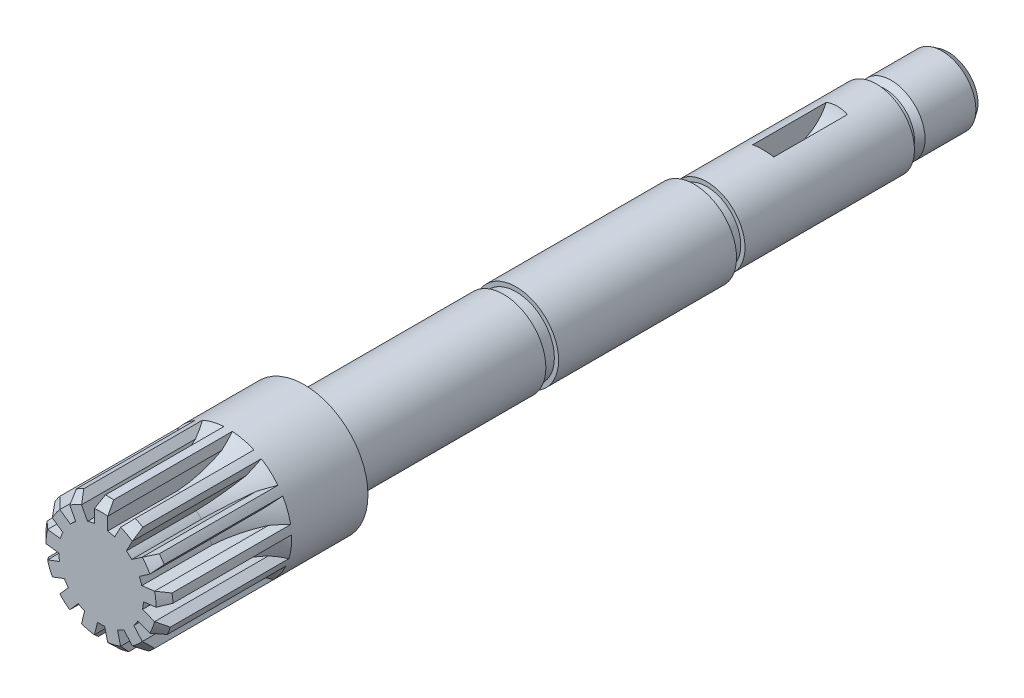
SolidWorks part; units mm, degrees
ref_plane "Спереди" through (0, 0, 0) normal (0, 0, 1) x (1, 0, 0)
ref_plane "Сверху" through (0, 0, 0) normal (0, 1, 0) x (1, 0, 0)
ref_plane "Справа" through (0, 0, 0) normal (1, 0, 0) x (0, 0, -1)
other "Configuration Table"
sketch "Эскиз1" plane through (0, 0, 0) normal (1, 0, 0) x (0, 0, -1)
  line L0 (-95, 0) -> (105, 0) construction
  line L1 (105, 0) -> (105, 7)
  line L2 (105, 7) -> (103.5, 8)
  line L3 (103.5, 8) -> (91.5, 8)
  line L4 (91.5, 8) -> (90, 7)
  line L5 (90, 7) -> (88, 7)
  line L6 (88, 7) -> (88, 9)
  line L7 (88, 9) -> (48, 9)
  line L8 (48, 9) -> (48, 8)
  line L9 (48, 8) -> (45, 8)
  line L10 (45, 8) -> (45, 10)
  line L11 (45, 10) -> (3, 10)
  line L12 (3, 10) -> (3, 9)
  line L13 (3, 9) -> (0, 9)
  line L14 (0, 9) -> (0, 10)
  line L15 (0, 10) -> (-46, 10)
  line L17 (-46, 10) -> (-46, 13)
  line L19 (-47, 15) -> (-65, 15)
  line L20 (-95, 0) -> (105, 0)
  line L22 (-47, 15) -> (-47, 14)
  line L23 (-78.52, 10) -> (-95, 10)
  line L25 (-95, 10) -> (-95, 0)
  arc A0 (-78.52, 10) -> (-65, 15) centre (-80.0634, 34.9523) ccw
  arc A1 (-46, 13) -> (-47, 14) centre (-47, 13) ccw
  dimension "D23" = 25
  dimension "D27" = 1
  dimension "D1" = 200
  dimension "D2" = 1.5
  dimension "D3" = 8
  dimension "D4" = 7
  dimension "D5" = 1.5
  dimension "D6" = 7
  dimension "D7" = 2
  dimension "D8" = 9
  dimension "D9" = 3
  dimension "D10" = 40
  dimension "D11" = 8
  dimension "D12" = 10
  dimension "D13" = 42
  dimension "D14" = 3
  dimension "D15" = 9
  dimension "D16" = 46
  dimension "D17" = 10
  dimension "D18" = 10
  dimension "D19" = 30
  dimension "D20" = 15
  dimension "D21" = 18
  dimension "D22" = 12
  dimension "D24" = 13
  dimension "D25" = 105
  dimension "D26" = 78.52
  dimension "D28" = 1
revolve "Повернуть1" add sketch "Эскиз1" angle 360 about L0
cosmetic thread "Условное изображение резьбы1" parameters "D2"=14
sketch "Эскиз2" plane through (0, 0, 95) normal (0, 0, 1) x (1, 0, 0)
  line L0 (1.567, 12.9052) -> (0.9938, 14.967)
  line L1 (-1.567, 12.9052) -> (-0.9938, 14.967)
  line L2 (1.567, 12.9052) -> (1.567, 9.8765)
  line L3 (-1.567, 12.9052) -> (-1.567, 9.8765)
  arc A0 (1.567, 12.9052) -> (-1.567, 12.9052) centre (0, 0) ccw construction
  arc A1 (0.9938, 14.967) -> (-0.9938, 14.967) centre (0, 0) ccw
  arc A2 (1.567, 9.8765) -> (-1.567, 9.8765) centre (0, 0) ccw
  circle A3 centre (0, 0) radius 10 construction
  point P4 (0, 5.4777)
  dimension "D1" = 13
  dimension "D2" = 15
  dimension "D3" = 10
  dimension "D4" = 0.9938
  dimension "D5" = 1.567
  dimension "D6" = 5.4777
extrude "Бобышка-Вытянуть1" add sketch "Эскиз2" against normal up to next
chamfer "Фаска1" distance 2 angle 45 1 edges at (0, 15, 95)
pattern_circular "Круговой массив1" count 13 over 360 about axis through (0, 0, 0) along (0, 0, 1) of "Бобышка-Вытянуть1", "Фаска1"
sketch "Эскиз3" plane through (0, 0, 0) normal (1, 0, 0) x (0, 0, -1)
  line L0 (70, 3) -> (70, 9) construction
  line L2 (88, -9) -> (88, 9) construction
  line L4 (60.7129, 10.5) -> (79.2871, 10.5)
  arc A0 (60.7129, 10.5) -> (79.2871, 10.5) centre (70, 12.5) ccw
  dimension "D4" = 9.5
  dimension "D1" = 18
  dimension "D2" = 7.5
  dimension "D3" = 6
  dimension "D5" = 10.5
extrude "Вырез-Вытянуть1" cut sketch "Эскиз3" against normal mid plane 5
